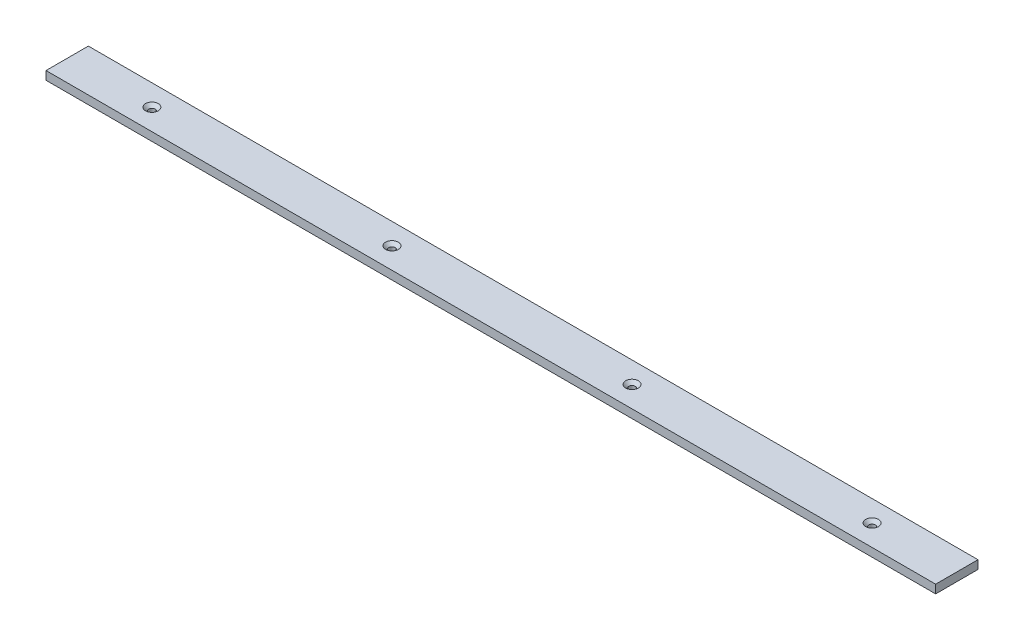
SolidWorks part; units mm, degrees
material "Aluminium"
ref_plane "Front Plane" through (0, 0, 0) normal (0, 0, 1) x (1, 0, 0)
ref_plane "Top Plane" through (0, 0, 0) normal (0, 1, 0) x (1, 0, 0)
ref_plane "Right Plane" through (0, 0, 0) normal (1, 0, 0) x (0, 0, -1)
sketch "Sketch1" plane through (0, 0, 0) normal (0, 1, 0) x (1, 0, 0)
  line L0 (0, 15) -> (0, -15) construction
  line L1 (-315, 15) -> (315, 15)
  line L2 (-315, 15) -> (-315, -15)
  line L3 (-315, -15) -> (315, -15)
  line L4 (315, 15) -> (315, -15)
  dimension "D1" = 30
  dimension "D2" = 630
extrude "Boss-Extrude1" add sketch "Sketch1" along normal blind 6
hole_wizard "M3 Clearance Hole1" [suppressed] positions "Sketch3" profile "Sketch2" hole size "M3" standard "DIN"
sketch "Sketch3" plane through (0, 6, 0) normal (0, 1, 0) x (1, 0, 0)
  line L0 (-315, 15) -> (-315, -15) construction
  line L1 (-315, 0) -> (-300, 0) construction
  point P0 (-300, 0)
  dimension "D1" = 15
sketch "Sketch2" plane through (-300, 6, 0) normal (1, 0, 0) x (0, 0, 1)
  line L0 (0, 0) -> (0, 6)
  line L1 (0, 6) -> (1.8, 6)
  line L2 (1.8, 6) -> (1.8, 0)
  line L5 (1.8, 0) -> (0, 0)
  line L11 (0, -6.35) -> (0, 107.95) construction
  dimension "Thru Hole Dia." = 3.6
  dimension "Thru Hole Depth" = 6
pattern_linear "LPattern1" [suppressed] count 24 spacing 25
sketch "Sketch4" plane through (0, 6, 0) normal (0, 1, 0) x (1, 0, 0)
  line L0 (-255, 0) -> (-315, 0) construction
  line L1 (-315, 15) -> (-315, -15) construction
  circle A0 centre (-255, 0) radius 2.25
  dimension "D1" = 60
  dimension "D2" = 4.5
extrude "Cut-Extrude1" cut sketch "Sketch4" against normal through all
sketch "Sketch5" plane through (0, 6, 0) normal (0, 1, 0) x (1, 0, 0)
  circle A0 centre (-255, 0) radius 4.5
  dimension "D1" = 9
extrude "Cut-Extrude2" cut sketch "Sketch5" against normal through all draft 45
pattern_linear "LPattern2" count 4 spacing 170 along (1, 0, 0) of "Cut-Extrude2", "Cut-Extrude1"
